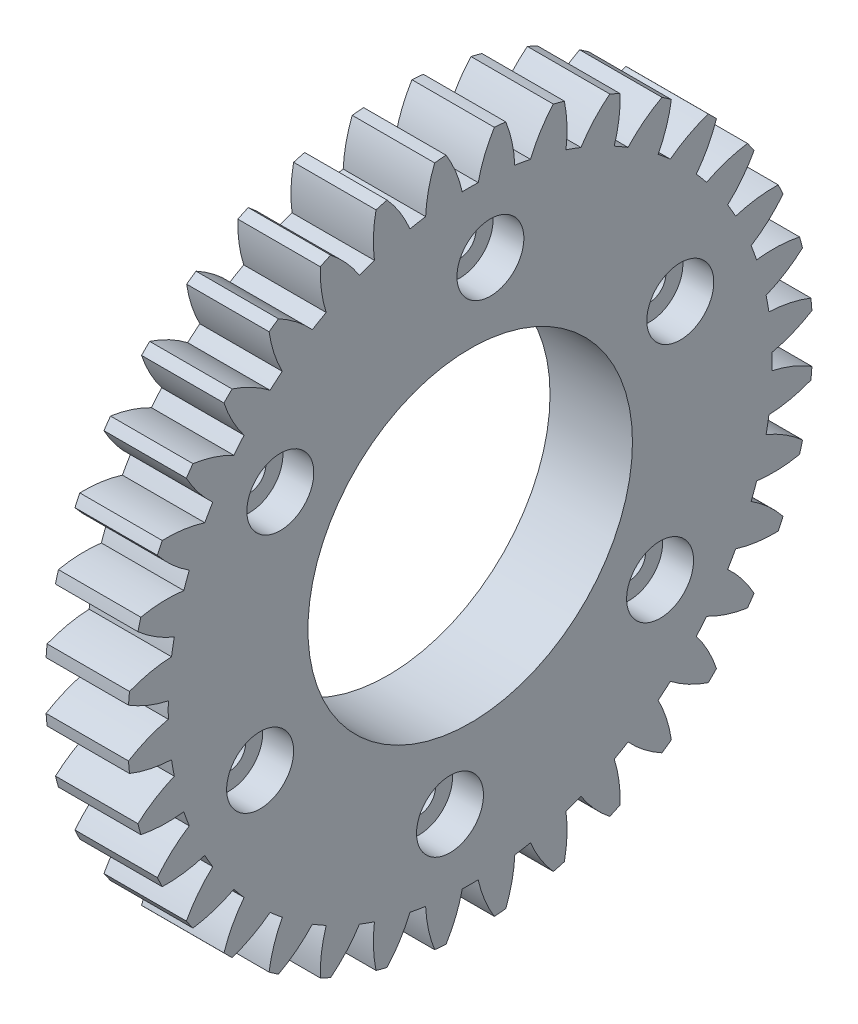
SolidWorks part; units mm, degrees
material "PLA personnalisé"
ref_plane "Plane1" through (0, 0, 0) normal (0, 0, 1) x (1, 0, 0)
ref_plane "Plane2" through (0, 0, 0) normal (0, 1, 0) x (1, 0, 0)
ref_plane "Plane3" through (0, 0, 0) normal (1, 0, 0) x (0, 0, -1)
other "Configuration Table"
sketch "HoldingSke" plane through (0, 0, 0) normal (0, 1, 0) x (1, 0, 0)
  line L0 (0, 0) -> (0.4623, -0.3359)
  line L1 (-15, 0) -> (100, 0) construction
  line L2 (0, 0) -> (-2.1039, 2.3779)
  line L3 (0, 0) -> (-11.863, 4.5341)
  line L4 (0, 0) -> (6.9867, 5.0761)
  line L5 (0, 0) -> (-46.8476, -17.4728)
  line L6 (0, 0) -> (-6.6317, -4.4744)
  line L7 (-2.1039, 2.3779) -> (8.6586, 51.2059)
  line L8 (-76.2, 54.61) -> (-74.8, 54.61)
  line L9 (-71.009, 38.7566) -> (-53.1078, 45.2721)
  line L10 (-76.2, 71.12) -> (104.1128, 71.12)
  line L11 (0, 0) -> (-8, 0)
  line L12 (-76.2, 101.6) -> (-76.147, 101.6)
  line L13 (24.9733, 27.94) -> (52.9518, 28.4284)
  line L14 (24.9733, 27.94) -> (24.9743, 27.94)
  line L15 (24.9733, 27.94) -> (100.4006, 29.5858)
  line L16 (-63.627, -1.75) -> (-12.827, -1.75)
  circle A0 centre (0, 0) radius 4
  circle A1 centre (0, 0) radius 29.3115
  circle A2 centre (0, 0) radius 37.5
  circle A3 centre (0, 0) radius 4
  dimension "MHD" = 58.623
  dimension "Hub_dia" = 75
  dimension "Bore" = 8
  dimension "MBD" = 8
  dimension "Num_teeth" = 36
  dimension "Pitch" = 0.5714
  dimension "Overall_len" = 50
  dimension "Show_teeth" = 36
  dimension "Thickness" = 8
  dimension "OAL" = 50.0001
  dimension "T_dim" = 1.4
  dimension "Ap" = 20
  dimension "H" = 19.05
  dimension "Pitch_radius" = 180.3128
  dimension "Width" = 8
  dimension "Backlash" = 0.053
  dimension "Addendum_fac" = 1
  dimension "Dedendum_fac" = 1.25
  dimension "Clearance_fac" = 0.25
  dimension "Dedendum_add" = 0.001
  dimension "Module" = 1.75
sketch "BasProSke" plane through (0, 0, 0) normal (0, 1, 0) x (1, 0, 0)
  line L0 (-10, 0) -> (60, 0) construction
  line L1 (0, 0) -> (0, 33.25)
  line L2 (0, 0) -> (8, 0)
  line L3 (8, 0) -> (8, 33.25)
  line L4 (8, 33.25) -> (0, 33.25)
  dimension "Thickness" = 8
  dimension "Diameter" = 66.5
revolve "Base-Revolve" add sketch "BasProSke" angle 360 about L0
sketch "TooCutSke" plane through (0, 0, 0) normal (1, 0, 0) x (0, 0, -1)
  line L1 (0, 0) -> (0, 107) construction
  line L2 (0, 0) -> (-1.4667, 31.4658) construction
  line L3 (0, 0) -> (-5.4863, 62.7083) construction
  line L4 (-1.4667, 31.4658) -> (-2.7431, 31.3542) construction
  arc A0 (0.7738, 29.3013) -> (-0.7738, 29.3013) centre (0, 0) ccw
  arc A1 (2.3593, 33.1917) -> (-2.3593, 33.1917) centre (0, 0) ccw
  circle A2 centre (0, 0) radius 31.5 construction
  circle A3 centre (0, 0) radius 29.6003 construction
  arc A4 (-0.7738, 29.3013) -> (-2.3593, 33.1917) centre (-13.0715, 26.5578) ccw
  arc A5 (2.3593, 33.1917) -> (0.7738, 29.3013) centre (13.0715, 26.5578) ccw
  dimension "Root_dia" = 58.623
  dimension "Overcut_dia" = 66.5508
  dimension "Pitch_dia" = 63
  dimension "Base_dia" = 59.2006
  dimension "Flank_rad" = 12.6
  dimension "Half_ang" = 5
  dimension "Half_CT" = 1.2813
extrude "ToothCut" cut sketch "TooCutSke" along normal through all
fillet "Breaks" [suppressed] radius 0.035
fillet "RootFillets" [suppressed] radius 0.4385
pattern_circular "TeethCuts" count 36 every 10 about axis through (-10, 0, 0) along (1, 0, 0) of "ToothCut", "RootFillets", "Breaks"
sketch "HubNeaOneSke" plane through (0, 0, 0) normal (-1, 0, 0) x (0, 0, 1)
  circle A0 centre (0, 0) radius 29.3115
  dimension "Diameter" = 58.623
extrude "HubNearOne" [suppressed] add sketch "HubNeaOneSke" along normal blind 42.0001
sketch "HubNeaBotSke" plane through (0, 0, 0) normal (-1, 0, 0) x (0, 0, 1)
  circle A0 centre (0, 0) radius 29.3115
  dimension "Diameter" = 58.623
extrude "HubNearBoth" [suppressed] add sketch "HubNeaBotSke" along normal blind 21
ref_plane "FarPln" through (8, 0, 0) normal (1, 0, 0) x (0, 0, -1)
sketch "HubFarSke" plane through (8, 0, 0) normal (1, 0, 0) x (0, 0, -1)
  circle A0 centre (0, 0) radius 29.3115
  dimension "Diameter" = 58.623
extrude "HubFar" [suppressed] add sketch "HubFarSke" along normal blind 21
sketch "BorSke" plane through (0, 0, 0) normal (1, 0, 0) x (0, 0, -1)
  circle A0 centre (0, 0) radius 4
  dimension "Diameter" = 8
extrude "Bore" cut sketch "BorSke" along normal mid plane 100.0001
sketch "KeySke" plane through (0, 0, 0) normal (1, 0, 0) x (0, 0, -1)
  line L0 (-1.5, 0) -> (-1.5, 5.4)
  line L1 (-1.5, 5.4) -> (1.5, 5.4)
  line L2 (1.5, 5.4) -> (1.5, 0)
  line L3 (0, 0) -> (0, 34) construction
  line L4 (-1.5, 0) -> (1.5, 0)
  dimension "Offset" = 5.4
  dimension "Width" = 3
extrude "Keyway" [suppressed] cut sketch "KeySke" along normal mid plane 100.0001
pattern_circular "Keyway2" [suppressed] count 2 every 90 about axis through (-10, 0, 0) along (1, 0, 0)
sketch "Esquisse1" plane through (8, 0, 0) normal (1, 0, 0) x (0, 0, -1)
  circle A0 centre (0, 0) radius 15.75
  dimension "D1" = 31.5
extrude "Enlèv. mat.-Extru.1" cut sketch "Esquisse1" against normal blind 10
sketch "Esquisse2" plane through (8, 0, 0) normal (1, 0, 0) x (0, 0, -1)
  line L0 (2.8979, 33.1235) -> (0, 0) construction
  line L1 (1.3673, 15.6288) -> (2.5547, 29.2)
  arc A0 (3.4508, 33.0704) -> (2.3442, 33.1673) centre (0, 0) ccw construction
  circle A1 centre (0, 0) radius 29.3115
  circle A2 centre (0, 0) radius 15.6885
  circle A3 centre (1.961, 22.4144) radius 1.6
  circle A4 centre (0, 0) radius 22.5
  dimension "D1" = 3.2
  dimension "D2" = 45
extrude "Enlèv. mat.-Extru.2" cut sketch "Esquisse2" against normal blind 10 contours A3
sketch "Esquisse3" plane through (8, 0, 0) normal (1, 0, 0) x (0, 0, -1)
  circle A0 centre (1.961, 22.4144) radius 3.25
  dimension "D1" = 6.5
extrude "Enlèv. mat.-Extru.3" cut sketch "Esquisse3" against normal blind 3
pattern_circular "Répétition circulaire2" count 6 over 360 about axis through (0, 0, 0) along (1, 0, 0) of "Enlèv. mat.-Extru.3", "Enlèv. mat.-Extru.2"
equation "' \"Module@HoldingSke\" = 6.35"
equation "' \"Num_teeth@HoldingSke\" = 12"
equation "' \"Ap@HoldingSke\" =  20"
equation "' \"Ap@HoldingSke\" = 20"
equation "' \"Width@HoldingSke\" = 0.5 * 25.4"
equation "' \"Hub_dia@HoldingSke\"= 1 * 25.4"
equation "' \"Hub_dia@HoldingSke\" = 1 * 25.4"
equation "' \"Overall_len@HoldingSke\" = 1.0 * 25.4"
equation "' \"Bore@HoldingSke\" = 0.75 * 25.4"
equation "' \"T_dim@HoldingSke\" = 0.1 * 25.4"
equation "' \"Width@KeySke\" = 0.25 * 25.4"
equation "' \"Show_teeth@HoldingSke\" = 13"
equation "' \"Backlash@HoldingSke\" = 0.009 * 25.4"
equation "' \"Addendum_fac@HoldingSke\" = 1.0"
equation "' \"Dedendum_fac@HoldingSke\" = 1.25"
equation "' \"Dedendum_add@HoldingSke\" = 0.00005 * 25.4"
equation "' \"Clearance_fac@HoldingSke\" = 0.25"
equation "\"Pitch@HoldingSke\" = 1 / \"Module@HoldingSke\""
equation "\"Overcut_dia@TooCutSke\" = (\"Num_teeth@HoldingSke\" + 2 * \"Addendum_fac@HoldingSke\") / \"Pitch@HoldingSke\" + 0.002 * 25.4"
equation "\"Pitch_dia@TooCutSke\" = \"Num_teeth@HoldingSke\" / \"Pitch@HoldingSke\""
equation "\"Base_dia@TooCutSke\" = \"Num_teeth@HoldingSke\" / \"Pitch@HoldingSke\" * cos((\"Ap@HoldingSke\"  * 3.14159265 / 180))"
equation "\"Root_dia@TooCutSke\" = (\"Num_teeth@HoldingSke\" + 2) / \"Pitch@HoldingSke\" - 2 * (\"Addendum_fac@HoldingSke\" + \"Dedendum_fac@HoldingSke\") / \"Pitch@HoldingSke\" - \"Dedendum_add@HoldingSke\" * 2"
equation "\"Half_ang@TooCutSke\" = 180 / \"Num_teeth@HoldingSke\""
equation "\"Half_CT@TooCutSke\" = \"Num_teeth@HoldingSke\" / \"Pitch@HoldingSke\" * sin((3.14159265 / 2 / \"Num_teeth@HoldingSke\")) / 2 - 7 * \"Backlash@HoldingSke\" / 4"
equation "\"Flank_rad@TooCutSke\" = \"Num_teeth@HoldingSke\" / \"Pitch@HoldingSke\" / 5"
equation "\"Radius@RootFillets\" = \"Clearance_fac@HoldingSke\" / \"Pitch@HoldingSke\" + \"Dedendum_add@HoldingSke\""
equation "\"Break_rad@Breaks\" = 0.02 / \"Pitch@HoldingSke\""
equation "\"Thickness@HoldingSke\" = \"Width@HoldingSke\""
equation "\"OAL@HoldingSke\" = \"Thickness@HoldingSke\""
equation "\"MHD@HoldingSke\" = (\"Num_teeth@HoldingSke\" + 2) / \"Pitch@HoldingSke\" - 2 * (\"Addendum_fac@HoldingSke\" + \"Dedendum_fac@HoldingSke\")  / \"Pitch@HoldingSke\" - \"Dedendum_add@HoldingSke\" * 2"
equation "\"MBD@HoldingSke\" = (\"Num_teeth@HoldingSke\" + 2) / \"Pitch@HoldingSke\" - 2 * (\"Addendum_fac@HoldingSke\" + \"Dedendum_fac@HoldingSke\")  / \"Pitch@HoldingSke\" - \"Dedendum_add@HoldingSke\" * 2 - 0.002 * 25.4"
equation "\"MHD@HoldingSke\" = ((sgn( \"MHD@HoldingSke\" - \"Hub_dia@HoldingSke\" )-1)*( \"MHD@HoldingSke\" - \"Hub_dia@HoldingSke\" ))/-2+ \"Hub_dia@HoldingSke\""
equation "\"MBD@HoldingSke\" = ((sgn( \"MBD@HoldingSke\" - \"Bore@HoldingSke\" )-1)*( \"MBD@HoldingSke\" - \"Bore@HoldingSke\" ))/-2+ \"Bore@HoldingSke\""
equation "\"OAL@HoldingSke\" = ((sgn( \"OAL@HoldingSke\" - \"Overall_len@HoldingSke\" )+1)*( \"OAL@HoldingSke\" - \"Overall_len@HoldingSke\" ))/2 + \"Overall_len@HoldingSke\" + 0.000002 * 25.4"
equation "\"Num_teeth@TeethCuts\" = int( \"Show_teeth@HoldingSke\" ) + 1"
equation "\"Num_teeth@TeethCuts\" = ((sgn( \"Num_teeth@TeethCuts\" - \"Num_teeth@HoldingSke\" )-1)*( \"Num_teeth@TeethCuts\" - \"Num_teeth@HoldingSke\" ))/-2+ \"Num_teeth@HoldingSke\""
equation "\"Num_teeth@TeethCuts\" = ((sgn( \"Num_teeth@TeethCuts\" - 2.0)+1)*( \"Num_teeth@TeethCuts\" - 2.0))/2 +2.0"
equation "\"Angle@TeethCuts\" = 360.0 / \"Num_teeth@HoldingSke\""
equation "\"Diameter@BasProSke\" = (\"Num_teeth@HoldingSke\" + 2 * \"Addendum_fac@HoldingSke\") / \"Pitch@HoldingSke\""
equation "\"Thickness@BasProSke\"  = \"Thickness@HoldingSke\""
equation "' \"Fillet_rad@BasProSke\" =  \"Thickness@HoldingSke\" * 0.05"
equation "' \"Fillet_rad@BasProSke\" = \"Thickness@HoldingSke\" * 0.05"
equation "\"MHD@HoldingSke\" = ((sgn( \"MHD@HoldingSke\" - \"Root_dia@TooCutSke\" )-1)*( \"MHD@HoldingSke\" - \"Root_dia@TooCutSke\" ))/-2+ \"Root_dia@TooCutSke\""
equation "\"Diameter@HubNeaOneSke\" = \"MHD@HoldingSke\""
equation "\"Length@HubNearOne\" = \"OAL@HoldingSke\" - \"Thickness@BasProSke\""
equation "\"Diameter@HubNeaBotSke\" = \"MHD@HoldingSke\""
equation "\"Length@HubNearBoth\" = ( \"OAL@HoldingSke\" - \"Thickness@BasProSke\" ) / 2.0"
equation "\"Thickness@FarPln\" = \"Thickness@BasProSke\""
equation "\"Diameter@HubFarSke\" = \"MHD@HoldingSke\""
equation "\"Length@HubFar\" = ( \"OAL@HoldingSke\" - \"Thickness@BasProSke\" ) / 2.0"
equation "\"Diameter@BorSke\" = \"MBD@HoldingSke\""
equation "\"D1@Bore\" = \"OAL@HoldingSke\" * 2.0"
equation "\"D1@Keyway\" = \"OAL@HoldingSke\" * 2.0"
equation "\"Offset@KeySke\" = \"T_dim@HoldingSke\" + \"MBD@HoldingSke\" / 2.0"
